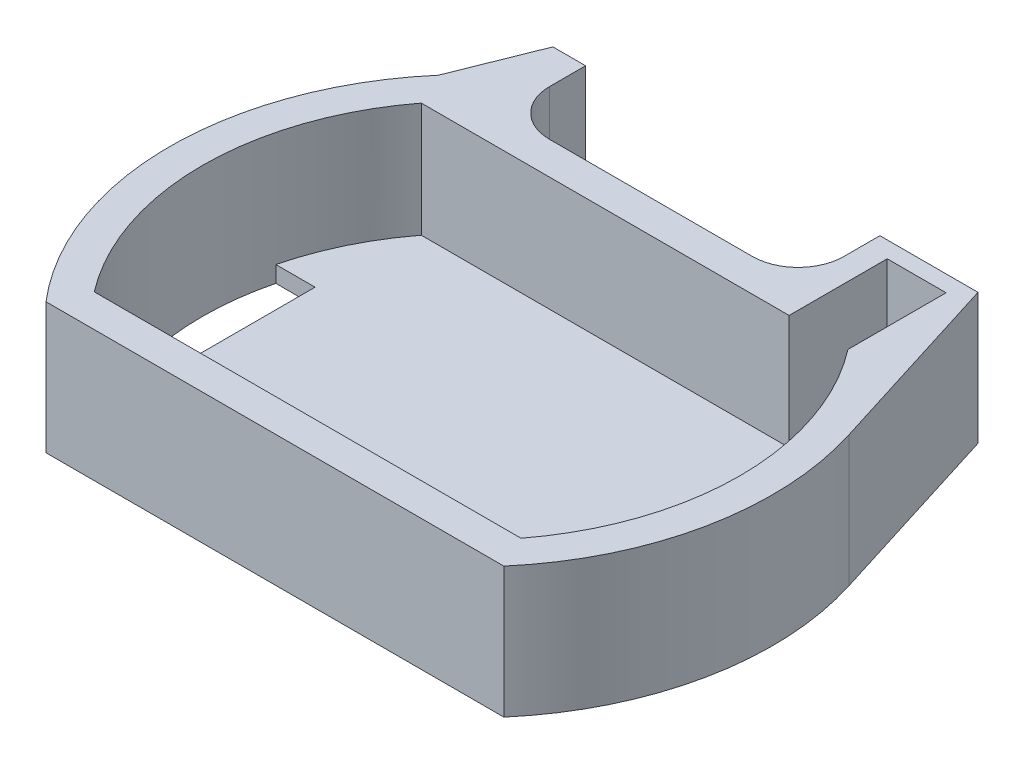
SolidWorks part; units mm, degrees
ref_plane "Front Plane" through (0, 0, 0) normal (0, 0, 1) x (1, 0, 0)
ref_plane "Top Plane" through (0, 0, 0) normal (0, 1, 0) x (1, 0, 0)
ref_plane "Right Plane" through (0, 0, 0) normal (1, 0, 0) x (0, 0, -1)
sketch "Sketch1" plane through (0, 0, 0) normal (0, 1, 0) x (1, 0, 0)
  line L0 (0, 76.2) -> (0, -76.2) construction
  line L1 (-88.9, -76.2) -> (88.9, -76.2)
  line L5 (-88.9, -76.2) -> (88.9, 76.2) construction
  line L6 (-88.9, 76.2) -> (88.9, -76.2) construction
  line L15 (-101.2509, 25.4) -> (-86.0109, 25.4)
  line L17 (-86.0109, 25.4) -> (-86.0109, -25.4)
  line L19 (-86.0109, -25.4) -> (-101.2509, -25.4)
  line L24 (0, 59.6666) -> (44.45, 59.6666) construction
  line L25 (0, 59.6666) -> (0, 27.9166) construction
  line L26 (0, 27.9166) -> (44.45, 27.9166) construction
  line L27 (44.45, 59.6666) -> (44.45, 27.9166) construction
  line L28 (86.0109, -25.4) -> (101.2509, -25.4)
  line L29 (86.0109, 25.4) -> (86.0109, -25.4)
  line L30 (101.2509, 25.4) -> (86.0109, 25.4)
  line L32 (15.7788, 14.5728) -> (96.7788, 14.5728) construction
  line L33 (15.7788, 14.5728) -> (15.7788, -10.4272) construction
  line L34 (15.7788, -10.4272) -> (96.7788, -10.4272) construction
  line L35 (96.7788, 14.5728) -> (96.7788, -10.4272) construction
  line L36 (-98.2629, 14.5728) -> (-17.2629, 14.5728) construction
  line L37 (-98.2629, 14.5728) -> (-98.2629, -10.4272) construction
  line L38 (-98.2629, -10.4272) -> (-17.2629, -10.4272) construction
  line L39 (-17.2629, 14.5728) -> (-17.2629, -10.4272) construction
  line L41 (-33.8081, -17.729) -> (34.1919, -17.729) construction
  line L42 (-33.8081, -17.729) -> (-33.8081, -52.729) construction
  line L43 (-33.8081, -52.729) -> (34.1919, -52.729) construction
  line L44 (34.1919, -17.729) -> (34.1919, -52.729) construction
  line L45 (-63.5, 107.95) -> (-63.5, 76.2)
  line L47 (63.5, 107.95) -> (63.5, 76.2)
  line L48 (-63.5, 76.2) -> (63.5, 76.2)
  line L49 (-88.9, 76.2) -> (-76.2, 107.95)
  line L50 (-76.2, 107.95) -> (-63.5, 107.95)
  line L51 (88.9, 107.95) -> (63.5, 107.95)
  line L53 (111.7418, 34.9773) -> (88.9, 107.95)
  arc A0 (-88.9, 76.2) -> (-88.9, -76.2) centre (0, 0) ccw
  arc A4 (-101.2509, 25.4) -> (-101.2509, -25.4) centre (0, 0) ccw
  arc A5 (-79.2574, 67.9349) -> (-79.2574, -67.9349) centre (0, 0) ccw construction
  arc A6 (101.2509, 25.4) -> (101.2509, -25.4) centre (0, 0) cw
  arc A7 (111.7418, 34.9773) -> (88.9, -76.2) centre (0, 0) cw
  point P0 (0, 0)
  point P18 (101.2509, 107.95)
  point P46 (117.0882, 0)
  dimension "D1" = 177.8
  dimension "D2" = 12.7
  dimension "D3" = 152.4
  dimension "D4" = 31.75
  dimension "D5" = 44.45
  dimension "D6" = 50.8
  dimension "D7" = 15.24
  dimension "D8" = 81
  dimension "D9" = 25
  dimension "D10" = 81
  dimension "D11" = 25
  dimension "D12" = 35
  dimension "D13" = 68
  dimension "D14" = 12.7
  dimension "D15" = 127
  dimension "D16" = 31.75
  dimension "D17" = 25.4
extrude "Boss-Extrude1" add sketch "Sketch1" along normal blind 6.35
sketch "Sketch2" plane through (0, 6.35, 0) normal (0, 1, 0) x (1, 0, 0)
  line L5 (-88.9, -76.2) -> (88.9, -76.2) construction
  line L11 (-88.9, -76.2) -> (88.9, -76.2)
  line L15 (63.5, 107.95) -> (63.5, 76.2) construction
  line L17 (-63.5, 76.2) -> (-63.5, 107.95) construction
  line L18 (63.5, 76.2) -> (-63.5, 76.2) construction
  line L20 (63.5, 107.95) -> (63.5, 76.2)
  line L22 (-63.5, 76.2) -> (-63.5, 107.95)
  line L23 (63.5, 76.2) -> (-63.5, 76.2)
  line L28 (-82.8532, -63.5) -> (82.8532, -63.5)
  line L29 (-88.9, -63.5) -> (88.9, -63.5) construction
  line L30 (-82.8532, 63.5) -> (82.8532, 63.5)
  line L32 (88.9, 107.95) -> (63.5, 107.95) construction
  line L33 (-63.5, 107.95) -> (-76.2, 107.95) construction
  line L34 (-76.2, 107.95) -> (-88.9, 76.2) construction
  line L36 (88.9, 107.95) -> (63.5, 107.95)
  line L37 (-63.5, 107.95) -> (-76.2, 107.95)
  line L38 (-76.2, 107.95) -> (-88.9, 76.2)
  line L39 (111.7418, 34.9773) -> (88.9, 107.95) construction
  line L40 (111.7418, 34.9773) -> (88.9, 107.95)
  arc A26 (-82.8532, 63.5) -> (-82.8532, -63.5) centre (0, 0) ccw
  arc A27 (82.8532, -63.5) -> (82.8532, 63.5) centre (0, 0) ccw
  arc A29 (-88.9, 76.2) -> (-88.9, -76.2) centre (0, 0) ccw construction
  arc A31 (-88.9, 76.2) -> (-88.9, -76.2) centre (0, 0) ccw
  arc A32 (88.9, -76.2) -> (111.7418, 34.9773) centre (0, 0) ccw construction
  arc A33 (88.9, -76.2) -> (111.7418, 34.9773) centre (0, 0) ccw
  point P22 (86.8138, 57.9678)
  dimension "D3" = 12.7
  dimension "D1" = 12.7
extrude "Boss-Extrude2" add sketch "Sketch2" along normal blind 44.45
sketch "Sketch4" plane through (0, 50.8, 0) normal (0, 1, 0) x (1, 0, 0)
  line L0 (63.5, 107.95) -> (50.8, 107.95)
  line L1 (50.8, 107.95) -> (50.8, 76.2)
  line L2 (63.5, 76.2) -> (-63.5, 76.2) construction
  line L3 (50.8, 76.2) -> (63.5, 76.2)
  line L4 (63.5, 76.2) -> (63.5, 107.95)
  line L5 (-63.5, 76.2) -> (-63.5, 107.95) construction
  dimension "D1" = 114.3
extrude "Boss-Extrude4" add sketch "Sketch4" against normal up to surface (50.8 mm away) up to face at (-94.4152, 0, 0)
sketch "Sketch5" plane through (0, 50.8, 0) normal (0, 1, 0) x (1, 0, 0)
  line L0 (59.9932, 63.5) -> (59.9932, 101.6)
  line L1 (82.8532, 63.5) -> (-82.8532, 63.5) construction
  line L2 (59.9932, 101.6) -> (82.8532, 101.6)
  line L3 (82.8532, 63.5) -> (82.8532, 101.6)
  line L5 (50.8, 76.2) -> (-63.5, 76.2) construction
  line L6 (59.9932, 63.5) -> (82.8532, 63.5)
  dimension "D1" = 25.4
  dimension "D2" = 22.86
extrude "Cut-Extrude1" cut sketch "Sketch5" against normal up to surface (44.45 mm away) up to face at (0, 6.35, 0)
fillet "Fillet3" radius 17.78 2 edges at (50.8, 25.4, -76.2) (-63.5, 25.4, -76.2)
ref_plane "Plane1" through (57.15, 0, 0) normal (1, 0, 0) x (0, 0, -1)
